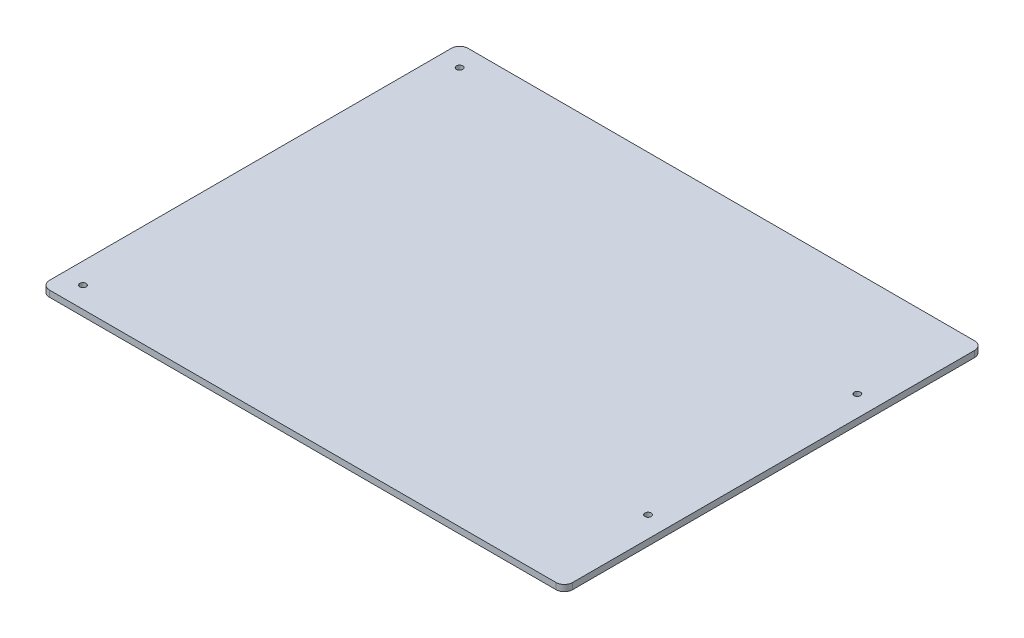
SolidWorks part; units mm, degrees
ref_plane "Front Plane" through (0, 0, 0) normal (0, 0, 1) x (1, 0, 0)
ref_plane "Top Plane" through (0, 0, 0) normal (0, 1, 0) x (1, 0, 0)
ref_plane "Right Plane" through (0, 0, 0) normal (1, 0, 0) x (0, 0, -1)
sketch "Sketch1" plane through (0, 0, 0) normal (0, 1, 0) x (1, 0, 0)
  line L0 (-125, 0) -> (125, 0) construction
  line L1 (-125, 100) -> (125, 100)
  line L2 (-125, 100) -> (-125, -100)
  line L3 (-125, -100) -> (125, -100)
  line L4 (125, 100) -> (125, -100)
  line L5 (-125, 100) -> (125, -100) construction
  line L6 (-125, -100) -> (125, 100) construction
  circle A0 centre (-115, 90) radius 1.5
  circle A1 centre (115, 50) radius 1.5
  circle A2 centre (115, -50) radius 1.5
  circle A3 centre (-115, -90) radius 1.5
  point P0 (0, 0)
  dimension "D5" = 3
  dimension "D1" = 200
  dimension "D2" = 250
  dimension "D3" = 10
  dimension "D4" = 10
  dimension "D6" = 50
  dimension "D7" = 10
extrude "Boss-Extrude1" add sketch "Sketch1" along normal blind 3
fillet "Fillet1" radius 4 4 edges at (125, 1.5, 100) (125, 1.5, -100) (-125, 1.5, -100) (-125, 1.5, 100)
